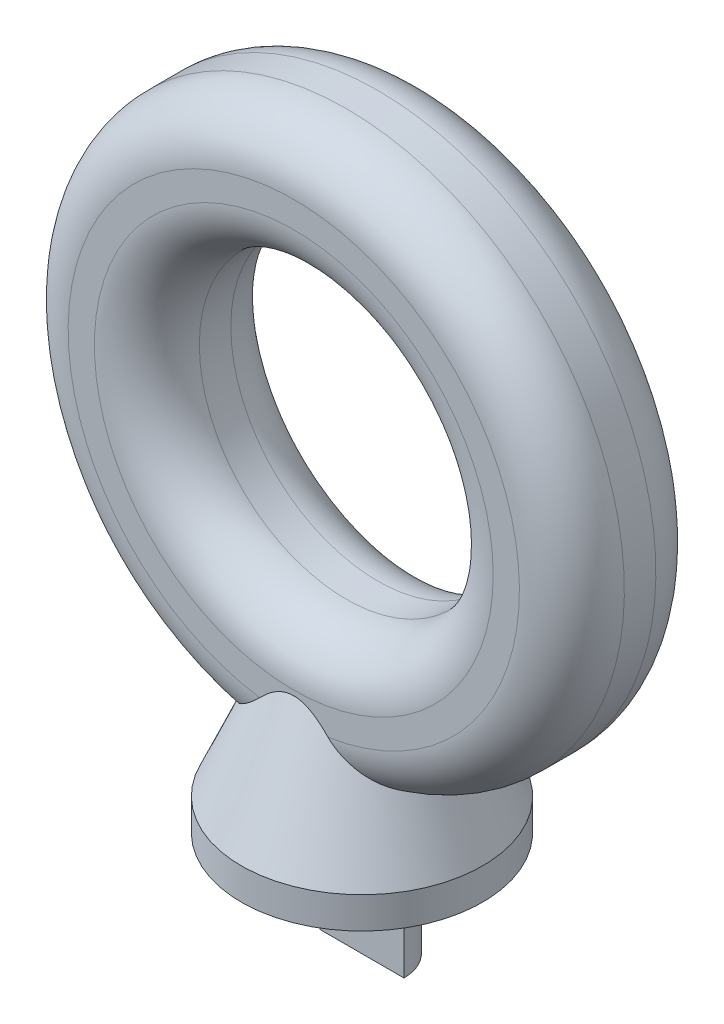
SolidWorks part; units mm, degrees
ref_plane "Plano frontal" through (0, 0, 0) normal (0, 0, 1) x (1, 0, 0)
ref_plane "Plano superior" through (0, 0, 0) normal (0, 1, 0) x (1, 0, 0)
ref_plane "Plano direito" through (0, 0, 0) normal (1, 0, 0) x (0, 0, -1)
sketch "Esboço2" plane through (0, 0, 0) normal (0, 0, 1) x (1, 0, 0)
  circle A0 centre (0, 0) radius 26.5
  circle A1 centre (0, 0) radius 14
  dimension "D1" = 53
  dimension "D2" = 28
extrude "Ressalto-extrusão1" add sketch "Esboço2" along normal mid plane 13
fillet "Filete1" radius 5 4 edges at (14, 0, -6.5) (26.5, 0, -6.5) (14, 0, 6.5) (26.5, 0, 6.5)
sketch "Esboço3" plane through (0, 0, 0) normal (0, 0, 1) x (1, 0, 0)
  line L0 (0, 0) -> (0, -44) construction
  line L1 (0, -16) -> (5, -16)
  line L2 (5, -16) -> (11.5, -31)
  line L3 (11.5, -31) -> (11.5, -34)
  line L4 (11.5, -34) -> (4, -34)
  line L5 (4, -34) -> (4, -44)
  line L6 (0, -44) -> (4, -44)
  circle A0 centre (0, 0) radius 14 construction
  circle A1 centre (0, 0) radius 14
  point P11 (0, -14)
  dimension "D1" = 23
  dimension "D2" = 10
  dimension "D3" = 3
  dimension "D4" = 20
  dimension "D5" = 10
  dimension "D6" = 8
  dimension "D7" = 2
revolve "Revolução7" add sketch "Esboço3" angle 360 about L0
sketch "Esboço4" plane through (0, -44, 0) normal (0, -1, 0) x (1, 0, 0)
  line L1 (-4, 0) -> (5.7675, 0)
  line L2 (-4, 0) -> (-4, 5.9031)
  line L3 (-4, 5.9031) -> (5.7675, 5.9031)
  line L4 (5.7675, 0) -> (5.7675, 5.9031)
  circle A0 centre (0, 0) radius 4 construction
extrude "Corte-extrusão1" cut sketch "Esboço4" against normal blind 5
